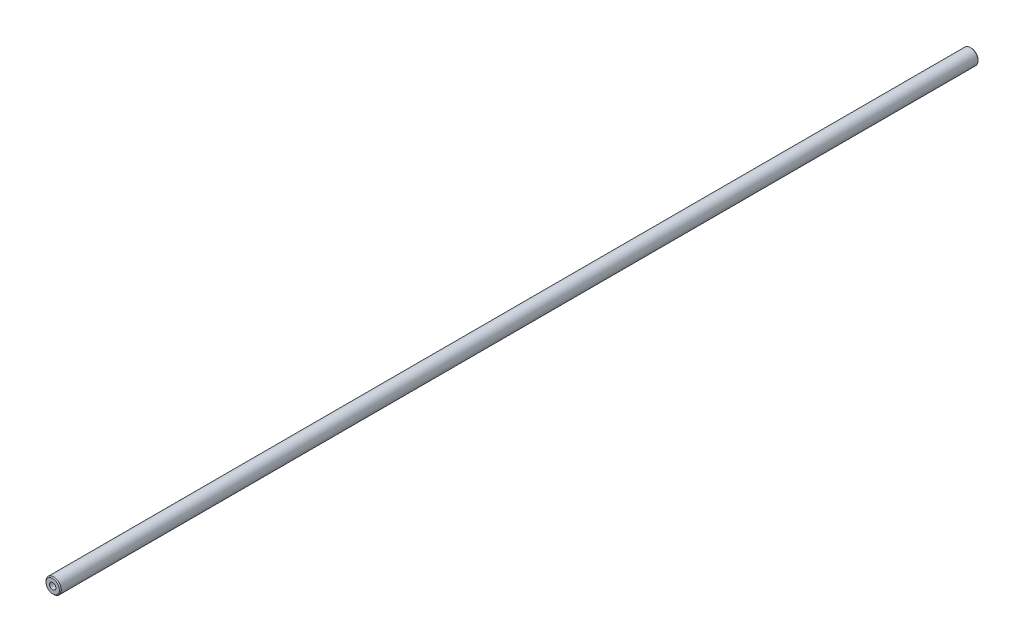
SolidWorks part; units mm, degrees
material "Acier inoxydable chromé"
ref_plane "Face" through (0, 0, 0) normal (0, 0, 1) x (1, 0, 0)
ref_plane "Dessus" through (0, 0, 0) normal (0, 1, 0) x (1, 0, 0)
ref_plane "Droite" through (0, 0, 0) normal (1, 0, 0) x (0, 0, -1)
sketch "Esquisse1" plane through (0, 0, 0) normal (0, 0, 1) x (1, 0, 0)
  circle A0 centre (0, 0) radius 4
  dimension "D1" = 8
extrude "Boss.-Extru.1" add sketch "Esquisse1" along normal blind 480
chamfer "Chanfrein1" distance 0.5 angle 45 2 edges at (4, 0, 480) (4, 0, 0)
hole_wizard "Trou taraudé M41" positions "Esquisse3" profile "Esquisse2" tap size "M4" standard "Iso"
sketch "Esquisse3" plane through (0, 0, 480) normal (0, 0, 1) x (1, 0, 0)
  point P0 (0, 0)
sketch "Esquisse2" plane through (0, 0, 480) normal (1, 0, 0) x (0, -1, 0)
  line L0 (0, 0) -> (0, 12.4914)
  line L1 (0, 12.4914) -> (1.65, 11.5)
  line L2 (1.65, 11.5) -> (1.65, 0)
  line L5 (1.65, 0) -> (0, 0)
  line L10 (0, 12.4914) -> (-1.65, 11.5) construction
  line L11 (0, -6.35) -> (0, 107.95) construction
  dimension "Diamètre du trou pour taraudage" = 3.3
  dimension "Profondeur du trou pour taraudage" = 11.5
  dimension "Angle de pointe" = 118
cosmetic thread "Filetage de perçage1" parameters "D1"=8, "D2"=4
hole_wizard "Trou taraudé M42" positions "Esquisse5" profile "Esquisse4" tap size "M4" standard "Iso"
sketch "Esquisse5" plane through (0, 0, 0) normal (0, 0, -1) x (-1, 0, 0)
  point P0 (0, 0)
sketch "Esquisse4" plane through (0, 0, 0) normal (1, 0, 0) x (0, 1, 0)
  line L0 (0, 0) -> (0, 12.4914)
  line L1 (0, 12.4914) -> (1.65, 11.5)
  line L2 (1.65, 11.5) -> (1.65, 0)
  line L5 (1.65, 0) -> (0, 0)
  line L10 (0, 12.4914) -> (-1.65, 11.5) construction
  line L11 (0, -6.35) -> (0, 107.95) construction
  dimension "Diamètre du trou pour taraudage" = 3.3
  dimension "Profondeur du trou pour taraudage" = 11.5
  dimension "Angle de pointe" = 118
cosmetic thread "Filetage de perçage2" parameters "D1"=8, "D2"=4
